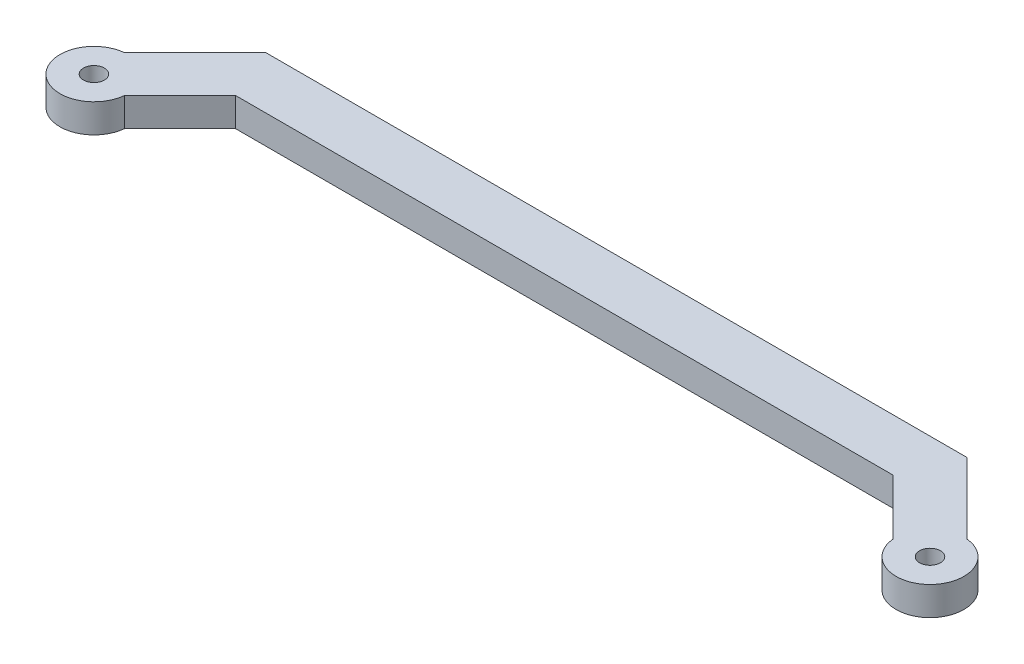
SolidWorks part; units mm, degrees
ref_plane "Plan de face" through (0, 0, 0) normal (0, 0, 1) x (1, 0, 0)
ref_plane "Plan de dessus" through (0, 0, 0) normal (0, 1, 0) x (1, 0, 0)
ref_plane "Plan de droite" through (0, 0, 0) normal (1, 0, 0) x (0, 0, -1)
sketch "Sketch1" plane through (0, 0, 0) normal (0, 1, 0) x (1, 0, 0)
  line L0 (80, -10) -> (65, 5) construction
  line L1 (65, 5) -> (-65, 5) construction
  line L2 (0, 5) -> (0, 0) construction
  line L3 (-62.9289, 0) -> (62.9289, 0)
  line L5 (67.0711, 10) -> (-67.0711, 10)
  line L6 (0, 5) -> (0, 0)
  line L7 (62.9289, 0) -> (73.5276, -10.5987)
  line L8 (67.0711, 10) -> (80.5987, -3.5276)
  line L9 (-80, -10) -> (-65, 5) construction
  line L10 (-67.0711, 10) -> (-80.5987, -3.5276)
  line L11 (-62.9289, 0) -> (-73.5276, -10.5987)
  arc A0 (73.5276, -10.5987) -> (80.5987, -3.5276) centre (80, -10) ccw
  circle A1 centre (80, -10) radius 2
  circle A2 centre (-80, -10) radius 2
  arc A3 (-73.5276, -10.5987) -> (-80.5987, -3.5276) centre (-80, -10) cw
  dimension "D5" = 13
  dimension "D6" = 4
  dimension "D1" = 135
  dimension "D3" = 15
  dimension "D4" = 5
  dimension "D7" = 10
  dimension "D10" = 5
  dimension "D8" = 10
  dimension "D2" = 160
extrude "Boss-Extrude1" add sketch "Sketch1" along normal blind 5.5 contours L3 L7 A0 L8 L5 L10 A3 L11 | A2 | A1
equation "\"D10@Sketch1\"=\"D7@Sketch1\"/2"
equation "\"Longueur1\"= 160mm"
equation "\"Longueur2\"= 180mm"
equation "\"D2@Sketch1\"=\"Longueur1\""
